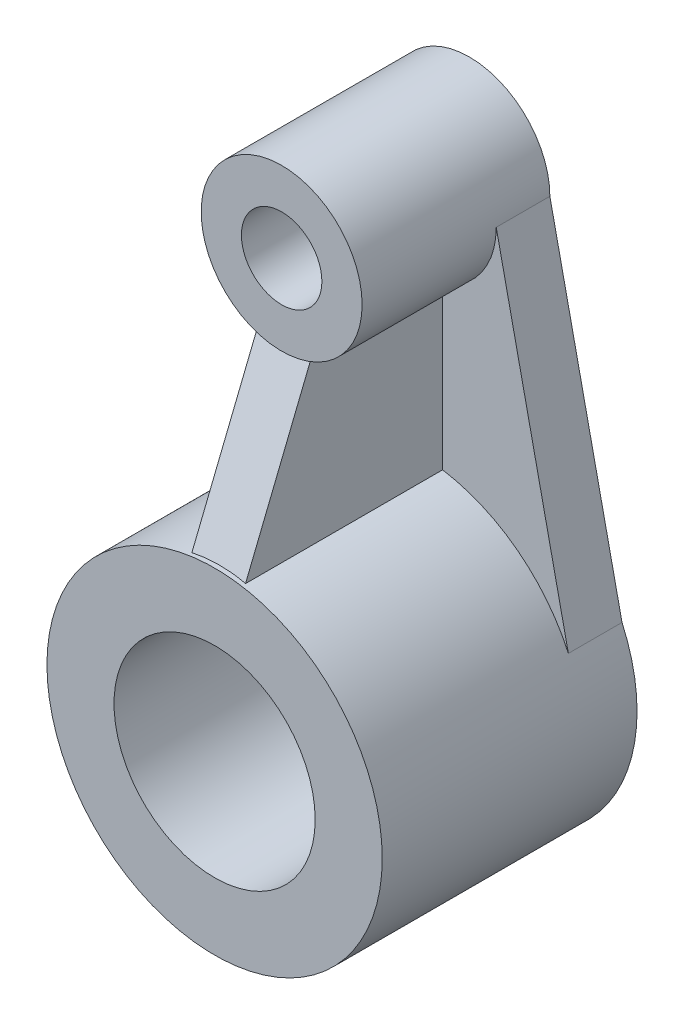
SolidWorks part; units mm, degrees
ref_plane "Front Plane" through (0, 0, 0) normal (0, 0, 1) x (1, 0, 0)
ref_plane "Top Plane" through (0, 0, 0) normal (0, 1, 0) x (1, 0, 0)
ref_plane "Right Plane" through (0, 0, 0) normal (1, 0, 0) x (0, 0, -1)
sketch "Sketch2" plane through (0, 0, 0) normal (0, 0, 1) x (1, 0, 0)
  circle A0 centre (0, 6.7261) radius 15
  circle A1 centre (0, 6.7261) radius 25
  dimension "D1" = 30
  dimension "D2" = 50
extrude "Boss-Extrude1" add sketch "Sketch2" against normal blind 38
sketch "Sketch4" plane through (0, 0, -30) normal (0, 0, 1) x (1, 0, 0)
  line L0 (22.6913, 66.7261) -> (-22.6913, 66.7261) construction
  circle A0 centre (0, 66.7261) radius 12
  circle A1 centre (0, 66.7261) radius 12
  circle A2 centre (0, 66.7261) radius 6
  dimension "D1" = 24
sketch "Sketch5" plane through (0, 0, -38) normal (0, 0, -1) x (-1, 0, 0)
  line L0 (-25, 6.7261) -> (-12, 66.7261)
  line L1 (12, 66.7261) -> (25, 6.7261)
  line L2 (-12, 66.7261) -> (12, 66.7261)
  circle A0 centre (0, 6.7261) radius 25 construction
  circle A1 centre (0, 66.7261) radius 12 construction
  arc A2 (-25, 6.7261) -> (25, 6.7261) centre (0, 6.7261) cw
  circle M2 centre (0, 6.7261) radius 25
extrude "Boss-Extrude3" add sketch "Sketch5" against normal blind 8 contours L2 L0 L1 M2
extrude "Boss-Extrude4" add sketch "Sketch4" along normal blind 20 contours A0 A2
sketch "Sketch6" plane through (0, 0, -30) normal (0, 0, -1) x (-1, 0, 0)
  line L0 (-12, 66.7261) -> (12, 66.7261) construction
  line L1 (-12, 66.7261) -> (12, 66.7261)
  arc A0 (-12, 66.7261) -> (12, 66.7261) centre (0, 66.7261) cw
  arc A1 (-6, 66.7261) -> (6, 66.7261) centre (0, 66.7261) cw
  arc A2 (6, 66.7261) -> (-6, 66.7261) centre (0, 66.7261) ccw construction
  arc M1 (12, 66.7261) -> (-12, 66.7261) centre (0, 66.7261) ccw
  line M2 (-12, 66.7261) -> (-6, 66.7261)
  arc M3 (-6, 66.7261) -> (6, 66.7261) centre (0, 66.7261) cw
  line M4 (6, 66.7261) -> (12, 66.7261)
extrude "Boss-Extrude5" add sketch "Sketch6" along normal blind 8 contours M4 M1 M2 M3
sketch "Sketch8" plane through (0, 0, -30) normal (0, 0, 1) x (1, 0, 0)
  line L0 (-6, 66.7261) -> (6, 66.7261)
  arc A0 (-6, 66.7261) -> (6, 66.7261) centre (0, 66.7261) ccw
extrude "Cut-Extrude1" cut sketch "Sketch8" against normal blind 71
sketch "Sketch9" plane through (0, 0, 0) normal (1, 0, 0) x (0, 0, -1)
  line L6 (10.8836, 56.8073) -> (30, 56.8073)
  line L7 (30, 17.0737) -> (30, 66.7261) construction
  line L9 (10.8836, 56.8073) -> (0, 29.8879)
  line L10 (0, 31.7261) -> (0, -18.2739) construction
  line L11 (0, 29.8879) -> (31.1746, 29.8879)
  line L12 (31.1746, 29.8879) -> (31.1746, 56.8073)
  line L13 (31.1746, 56.8073) -> (30, 56.8073)
extrude "Boss-Extrude8" add sketch "Sketch9" along normal mid plane 8
